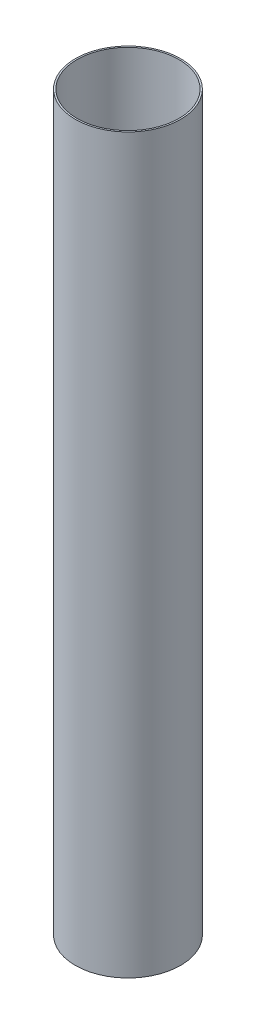
SolidWorks part; units mm, degrees
material "E-Glass Fiber"
ref_plane "Front Plane" through (0, 0, 0) normal (0, 0, 1) x (1, 0, 0)
ref_plane "Top Plane" through (0, 0, 0) normal (0, 1, 0) x (1, 0, 0)
ref_plane "Right Plane" through (0, 0, 0) normal (1, 0, 0) x (0, 0, -1)
sketch "Motor Mount Profile Sketch" plane through (0, 0, 0) normal (0, 1, 0) x (1, 0, 0)
  circle A0 centre (0, 0) radius 51.1048
  circle A1 centre (0, 0) radius 49.53
  dimension "D1" = 102.2096
  dimension "D2" = 99.06
extrude "Motor Mount Body" add sketch "Motor Mount Profile Sketch" along normal blind 711.2
equation "\"Length\"=28"
equation "\"Outer Diameter\"= 4.024"
equation "\"Inner Diameter\"= 3.9"
equation "\"Wall Thickness\"= 0.062"
equation "\"D1@Motor Mount Profile Sketch\" = \"Outer Diameter\""
equation "\"D2@Motor Mount Profile Sketch\" = \"Inner Diameter\""
equation "\"D1@Motor Mount Body\" = \"Length\""
